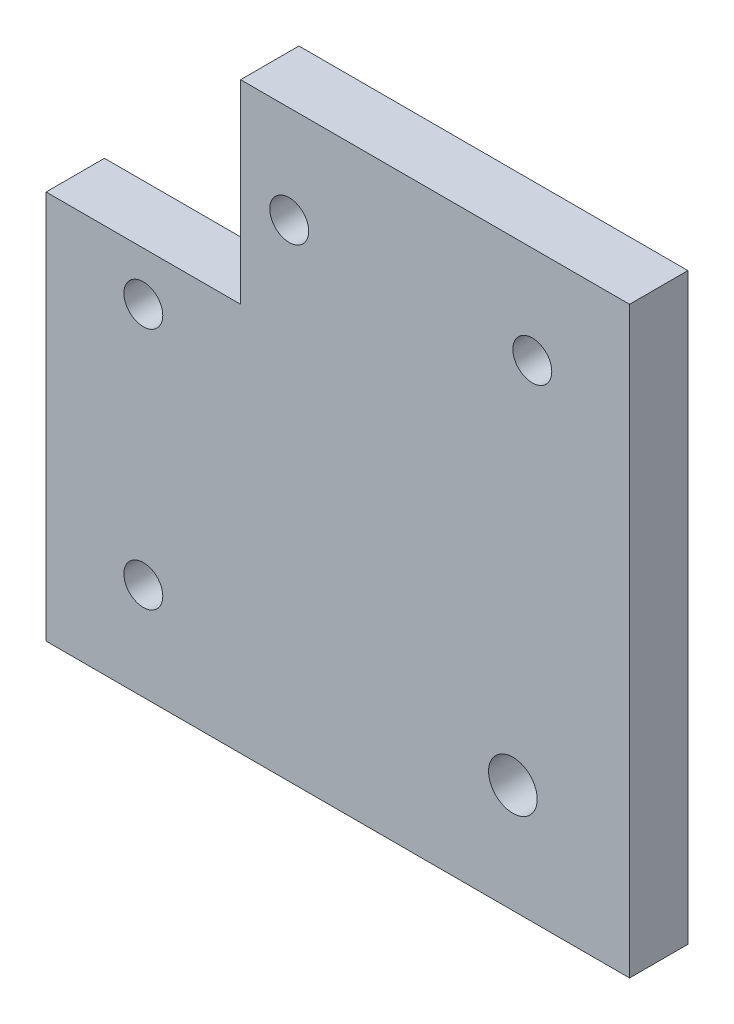
SolidWorks part; units mm, degrees
ref_plane "Front Plane" through (0, 0, 0) normal (0, 0, 1) x (1, 0, 0)
ref_plane "Top Plane" through (0, 0, 0) normal (0, 1, 0) x (1, 0, 0)
ref_plane "Right Plane" through (0, 0, 0) normal (1, 0, 0) x (0, 0, -1)
sketch "Sketch1" plane through (0, 0, 0) normal (0, 0, 1) x (1, 0, 0)
  line L1 (29.3431, 0) -> (60, 0)
  line L2 (0, -29.3431) -> (0, -60)
  line L3 (0, -60) -> (20, -60)
  line L4 (60, 0) -> (60, -20)
  line L5 (10, -60) -> (10, -50) construction
  line L6 (10, -50) -> (10, -25) construction
  line L7 (10, -25) -> (10, -10) construction
  line L8 (10, -10) -> (25, -10) construction
  line L9 (25, -10) -> (50, -10) construction
  line L10 (50, -10) -> (60, -10) construction
  line L13 (60, -20) -> (60, -60)
  line L14 (60, -60) -> (20, -60)
  line L16 (0, -29.3431) -> (0, -20)
  line L17 (20, 0) -> (29.3431, 0)
  line L18 (0, 0) -> (0, -20) construction
  line L19 (20, -20) -> (0, -20)
  line L20 (20, -20) -> (20, 0)
  line L23 (0, 0) -> (20, 0) construction
  circle A0 centre (50, -10) radius 2
  circle A1 centre (25, -10) radius 2
  circle A2 centre (10, -50) radius 2
  circle A3 centre (10, -25) radius 2
  circle A4 centre (48, -48.8332) radius 2.5
  dimension "D3" = 4
  dimension "D8" = 12
  dimension "D9" = 11.1668
  dimension "D10" = 5
  dimension "D11" = 29.3431
  dimension "D12" = 20
  dimension "D1" = 60
  dimension "D2" = 20
  dimension "D4" = 10
  dimension "D5" = 25
  dimension "D6" = 25
  dimension "D7" = 10
  dimension "D13" = 60
extrude "Boss-Extrude1" add sketch "Sketch1" along normal blind 6
